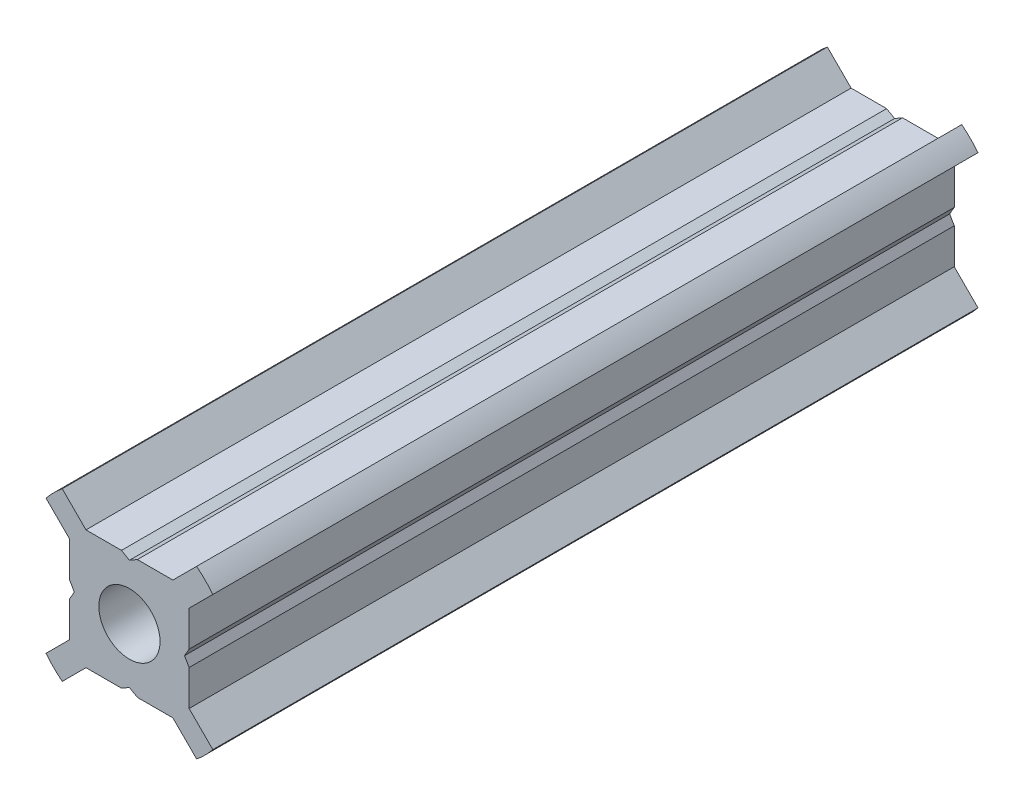
SolidWorks part; units mm, degrees
material "3.3535 (EN-AW 5754)"
ref_plane "Front Plane" through (0, 0, 0) normal (0, 0, 1) x (1, 0, 0)
ref_plane "Top Plane" through (0, 0, 0) normal (0, 1, 0) x (1, 0, 0)
ref_plane "Right Plane" through (0, 0, 0) normal (1, 0, 0) x (0, 0, -1)
sketch "Sketch1" plane through (0, 0, 0) normal (0, 0, 1) x (1, 0, 0)
  line L0 (10, 10) -> (4.6104, 10) construction
  line L1 (10, 10) -> (10, 4.6104) construction
  line L2 (10, -10) -> (10, -4.6104) construction
  line L3 (10, -10) -> (4.6104, -10) construction
  line L4 (10, 10) -> (10, 4.6104)
  line L5 (6.5607, 5.5) -> (8.2, 5.5)
  line L6 (5.5, 8.2) -> (5.5, 6.5607)
  line L7 (10, 10) -> (4.6104, 10)
  line L8 (10, 10) -> (10, 4.6104)
  line L9 (6.5607, 5.5) -> (3.9, 2.8393)
  line L10 (5.5, 6.5607) -> (2.8393, 3.9)
  line L11 (10, 4.6104) -> (8.2, 3.1)
  line L12 (4.6104, 10) -> (3.1, 8.2)
  line L13 (8.2, 3.1) -> (8.2, 5.5)
  line L14 (3.1, 8.2) -> (5.5, 8.2)
  line L15 (-6.5607, 5.5) -> (-8.2, 5.5)
  line L16 (6.5607, -5.5) -> (8.2, -5.5)
  line L17 (3.1, -8.2) -> (5.5, -8.2)
  line L18 (8.2, -3.1) -> (8.2, -5.5)
  line L19 (4.6104, -10) -> (3.1, -8.2)
  line L20 (10, -4.6104) -> (8.2, -3.1)
  line L21 (0.5196, -3.9) -> (0, -3.6)
  line L22 (0.5196, 3.9) -> (0, 3.6)
  line L23 (3.6, 0) -> (3.9, -0.5196)
  line L24 (3.9, 0.5196) -> (3.6, 0)
  line L25 (3.9, 0.5196) -> (3.9, 2.8393)
  line L26 (2.8393, 3.9) -> (0.5196, 3.9)
  line L27 (3.9, -2.8393) -> (3.9, -0.5196)
  line L28 (2.8393, -3.9) -> (0.5196, -3.9)
  line L29 (5.5, -6.5607) -> (2.8393, -3.9)
  line L30 (6.5607, -5.5) -> (3.9, -2.8393)
  line L31 (10, -10) -> (10, -4.6104)
  line L32 (10, -10) -> (4.6104, -10)
  line L33 (5.5, -8.2) -> (5.5, -6.5607)
  line L34 (-6.5607, -5.5) -> (-8.2, -5.5)
  line L35 (10, -10) -> (10, -4.6104)
  line L36 (0, 0) -> (0, 8.2) construction
  line L37 (-10, -10) -> (-4.6104, -10) construction
  line L38 (-10, -10) -> (-10, -4.6104) construction
  line L39 (-10, 10) -> (-10, 4.6104) construction
  line L40 (-10, 10) -> (-4.6104, 10) construction
  line L41 (-10, -10) -> (-10, -4.6104)
  line L43 (-5.5, -8.2) -> (-5.5, -6.5607)
  line L44 (-10, -10) -> (-4.6104, -10)
  line L45 (-10, -10) -> (-10, -4.6104)
  line L46 (-6.5607, -5.5) -> (-3.9, -2.8393)
  line L47 (-5.5, -6.5607) -> (-2.8393, -3.9)
  line L48 (-2.8393, -3.9) -> (-0.5196, -3.9)
  line L49 (-3.9, -2.8393) -> (-3.9, -0.5196)
  line L50 (-2.8393, 3.9) -> (-0.5196, 3.9)
  line L51 (-3.9, 0.5196) -> (-3.9, 2.8393)
  line L52 (-3.9, 0.5196) -> (-3.6, 0)
  line L53 (-3.6, 0) -> (-3.9, -0.5196)
  line L54 (-0.5196, 3.9) -> (0, 3.6)
  line L55 (-0.5196, -3.9) -> (0, -3.6)
  line L56 (-10, -4.6104) -> (-8.2, -3.1)
  line L57 (-4.6104, -10) -> (-3.1, -8.2)
  line L58 (-8.2, -3.1) -> (-8.2, -5.5)
  line L59 (-3.1, -8.2) -> (-5.5, -8.2)
  line L60 (-10, -10) -> (10, -10) construction
  line L61 (-10, -10) -> (-10, 10) construction
  line L62 (-3.1, 8.2) -> (-5.5, 8.2)
  line L63 (-8.2, 3.1) -> (-8.2, 5.5)
  line L64 (-4.6104, 10) -> (-3.1, 8.2)
  line L65 (-10, 4.6104) -> (-8.2, 3.1)
  line L66 (-5.5, 6.5607) -> (-2.8393, 3.9)
  line L67 (-6.5607, 5.5) -> (-3.9, 2.8393)
  line L68 (-10, 10) -> (-10, 4.6104)
  line L69 (-10, 10) -> (-4.6104, 10)
  line L70 (-5.5, 8.2) -> (-5.5, 6.5607)
  line L71 (-10, 10) -> (10, 10) construction
  line L72 (-10, 10) -> (-10, 4.6104)
  line L73 (10, -10) -> (10, 10) construction
  line L74 (-10, -10) -> (10, 10) construction
  line L75 (-10, 10) -> (10, -10) construction
  circle A0 centre (0, 0) radius 2
  circle A1 centre (0, 0) radius 7
  dimension "D7" = 4
  dimension "D16" = 14
  dimension "D1" = 20
  dimension "D2" = 5.3896
  dimension "D3" = 4.5
  dimension "D4" = 50
  dimension "D5" = 1.8
  dimension "D6" = 1.5104
  dimension "D8" = 5.5
  dimension "D9" = 120
  dimension "D10" = 0.3
  dimension "D11" = 2.3197
  dimension "D12" = 7.8
  dimension "D13" = 7.8
  dimension "D14" = 1.5
  dimension "D15" = 2.6607
extrude "Boss-Extrude1" add sketch "Sketch1" along normal blind 50 contours L70 L62 L64 L69 L68 L65 L63 L15 L67 L51 L52 L53 L49 L46 L34 L58 L56 L41 L44 L57 L59 L43 L47 L48 L55 L21 L28 L29 L33 L17 L19 L32 L31 L20 L18 L16 L30 L27 L23 L24 L25 L9 L5 L13 L11 L4 L7 L12 L14 L6 L10
